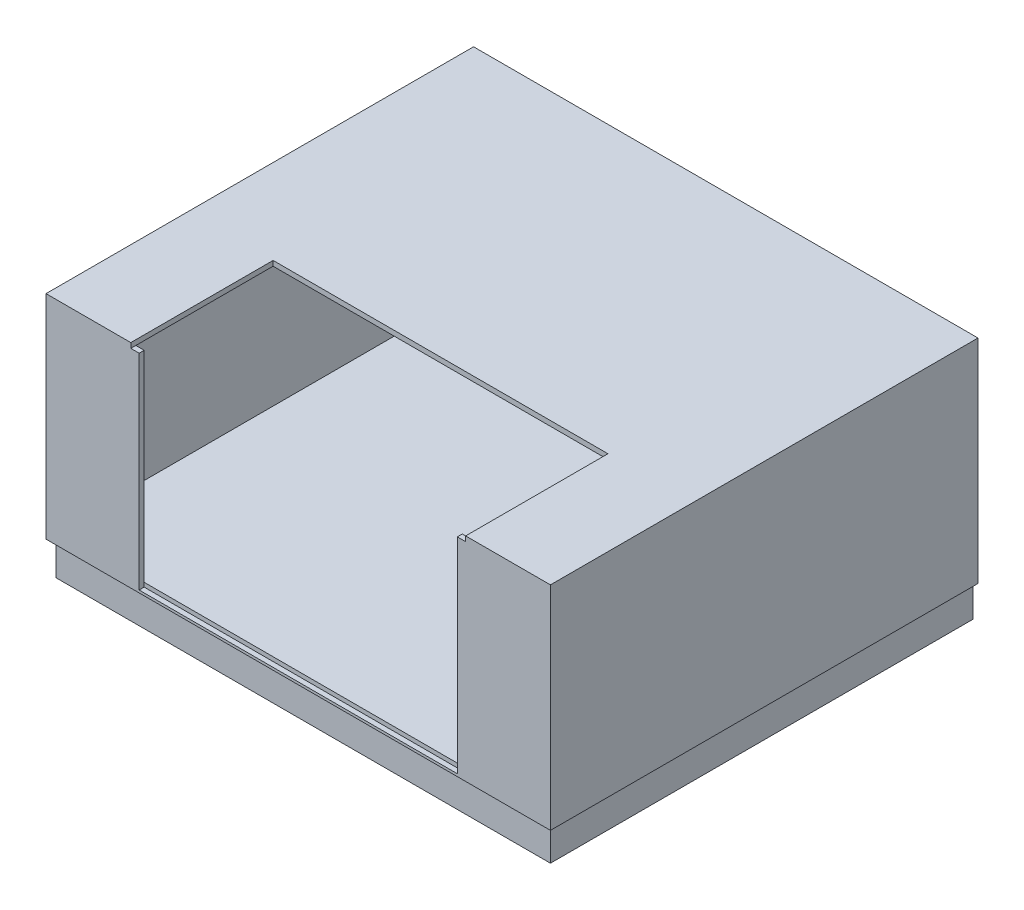
SolidWorks part; units mm, degrees
ref_plane "Front" through (0, 0, 0) normal (0, 0, 1) x (1, 0, 0)
ref_plane "Top" through (0, 0, 0) normal (0, 1, 0) x (1, 0, 0)
ref_plane "Right" through (0, 0, 0) normal (1, 0, 0) x (0, 0, -1)
ref_plane "Плоскость1" through (300, 0, 0) normal (1, 0, 0) x (0, 0, -1)
sketch "Эскиз1" plane through (0, 0, 0) normal (0, 1, 0) x (1, 0, 0)
  line L0 (300, -248.1333) -> (300, 248.1333) construction
  line L1 (-1.2872, -69.149) -> (601.2872, -69.149)
  line L2 (-1.2872, -69.149) -> (-1.2872, -573.9108)
  line L3 (-1.2872, -573.9108) -> (601.2872, -573.9108)
  line L4 (601.2872, -69.149) -> (601.2872, -573.9108)
  point P4 (300, -573.9108)
extrude "Бобышка-Вытянуть1" add sketch "Эскиз1" along normal blind 8
sketch "Эскиз2" plane through (0, 8, 0) normal (0, 1, 0) x (1, 0, 0)
  line L0 (4.7128, -69.149) -> (4.7128, -573.9108)
  line L1 (-1.2872, -69.149) -> (4.7128, -69.149)
  line L2 (-1.2872, -69.149) -> (-1.2872, -573.9108)
  line L3 (-1.2872, -573.9108) -> (4.7128, -573.9108)
  line L4 (601.2872, -69.149) -> (601.2872, -573.9108)
  line L6 (595.2872, -573.9108) -> (595.2872, -69.149)
  line L7 (595.2872, -69.149) -> (601.2872, -69.149)
  line L8 (595.2872, -573.9108) -> (601.2872, -573.9108)
  point P8 (0, 0)
  point P11 (0, 0)
  dimension "D1" = 6
  dimension "D2" = 6
extrude "Бобышка-Вытянуть2" add sketch "Эскиз2" along normal blind 240
sketch "Эскиз3" plane through (0, 248, 0) normal (0, 1, 0) x (1, 0, 0)
  line L1 (-1.2872, -69.149) -> (601.2872, -69.149)
  line L2 (-1.2872, -69.149) -> (-1.2872, -573.9108)
  line L3 (-1.2872, -573.9108) -> (601.2872, -573.9108)
  line L4 (601.2872, -69.149) -> (601.2872, -573.9108)
extrude "Бобышка-Вытянуть3" add sketch "Эскиз3" along normal blind 6
sketch3d "Трехмерный эскиз1"
  line L0 (-1.2872, 254, 321.5299) -> (601.2872, 254, 321.5299) construction
  line L1 (-1.2872, 254, 69.149) -> (-1.2872, 254, 573.9108) construction
  line L2 (601.2872, 254, 573.9108) -> (601.2872, 254, 69.149) construction
ref_plane "Плоскость2" through (0, 175.4955, 359.8191) normal (0, 0.4384, 0.8988) x (1, 0, 0)
sketch "Эскиз5" plane through (0, 0, 573.9108) normal (0, 0, 1) x (1, 0, 0)
  line L1 (-1.2872, 254) -> (601.2872, 254)
  line L2 (-1.2872, 254) -> (-1.2872, 0)
  line L3 (-1.2872, 0) -> (601.2872, 0)
  line L4 (601.2872, 254) -> (601.2872, 0)
extrude "Бобышка-Вытянуть4" add sketch "Эскиз5" along normal blind 6
sketch "Эскиз4" plane through (0, 254, 0) normal (0, 1, 0) x (1, 0, 0)
  line L2 (100, -579.9108) -> (100, -409.9108)
  line L3 (100, -409.9108) -> (500, -409.9108)
  line L4 (500, -579.9108) -> (500, -409.9108)
  line L5 (300, -69.149) -> (300, -579.9108) construction
  line L6 (601.2872, -69.149) -> (-1.2872, -69.149) construction
  line L11 (100, -579.9108) -> (500, -579.9108)
  line L15 (601.2872, -579.9108) -> (-1.2872, -579.9108) construction
  point P10 (300, -409.9108)
  dimension "D1" = 170
  dimension "D2" = 400
extrude "Вырез-Вытянуть4" cut sketch "Эскиз4" against normal up to surface (6 mm away) up to face at (300, 248, 321.5299)
sketch "Эскиз9" plane through (0, 0, 579.9108) normal (0, 0, 1) x (1, 0, 0)
  line L0 (500, 248) -> (100, 248) construction
  line L1 (110, 248) -> (490, 248)
  line L2 (110, 248) -> (110, 3)
  line L3 (110, 3) -> (490, 3)
  line L4 (490, 248) -> (490, 3)
  line L5 (300, 0) -> (300, 296.3453) construction
  line L6 (-1.2872, 0) -> (601.2872, 0) construction
  point P10 (300, 3)
  point P11 (0, 0)
  point P13 (0, 0)
  dimension "D1" = 10
  dimension "D2" = 245
extrude "Вырез-Вытянуть5" cut sketch "Эскиз9" against normal up to surface (6 mm away) up to face at (300, 168, 573.9108)
sketch "Эскиз12" plane through (0, 0, 0) normal (0, -1, 0) x (1, 0, 0)
  line L9 (601.2872, 69.149) -> (-1.2872, 69.149) construction
  line L10 (4.7128, 573.9108) -> (595.2872, 573.9108)
  line L11 (4.7128, 573.9108) -> (4.7128, 69.149)
  line L13 (595.2872, 573.9108) -> (595.2872, 69.149)
  line L14 (-1.2872, 69.149) -> (-1.2872, 579.9108) construction
  line L15 (-1.2872, 579.9108) -> (601.2872, 579.9108) construction
  line L16 (601.2872, 579.9108) -> (601.2872, 69.149) construction
  line L17 (595.2872, 69.149) -> (555.2872, 69.149)
  line L18 (555.2872, 69.149) -> (555.2872, 533.9108)
  line L19 (555.2872, 533.9108) -> (44.7128, 533.9108)
  line L20 (44.7128, 533.9108) -> (44.7128, 69.149)
  line L21 (44.7128, 69.149) -> (4.7128, 69.149)
  dimension "D1" = 6
  dimension "D2" = 6
  dimension "D3" = 6
  dimension "D4" = 40
  dimension "D5" = 40
  dimension "D6" = 40
extrude "Бобышка-Вытянуть8" add sketch "Эскиз12" along normal blind 40
equation "\"D3@Эскиз10\"=\"D1@Эскиз10\""
